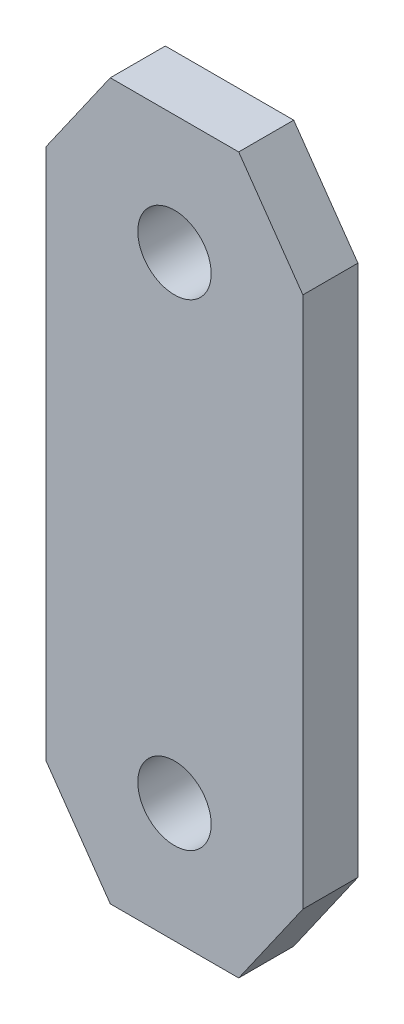
SolidWorks part; units mm, degrees
ref_plane "Płaszczyzna przednia" through (0, 0, 0) normal (0, 0, 1) x (1, 0, 0)
ref_plane "Płaszczyzna górna" through (0, 0, 0) normal (0, 1, 0) x (1, 0, 0)
ref_plane "Płaszczyzna prawa" through (0, 0, 0) normal (1, 0, 0) x (0, 0, -1)
sketch "Szkic1" plane through (0, 0, 0) normal (0, 0, 1) x (1, 0, 0)
  line L0 (7, 14.5) -> (3.5, 19.5)
  line L1 (3.5, -19.5) -> (-3.5, -19.5)
  line L2 (7, -14.5) -> (7, 14.5)
  line L3 (3.5, 19.5) -> (-3.5, 19.5)
  line L4 (-7, -14.5) -> (-7, 14.5)
  line L5 (7, -19.5) -> (-7, 19.5) construction
  line L6 (7, 19.5) -> (-7, -19.5) construction
  line L7 (-3.5, 19.5) -> (-7, 14.5)
  line L8 (-3.5, -19.5) -> (-7, -14.5)
  line L9 (7, -14.5) -> (3.5, -19.5)
  point P0 (0, 0)
  dimension "D1" = 39
  dimension "D2" = 14
  dimension "D3" = 3.5
  dimension "D4" = 5
  dimension "D5" = 3.5
  dimension "D6" = 5
  dimension "D7" = 3.5
  dimension "D8" = 5
  dimension "D9" = 3.5
  dimension "D10" = 5
extrude "Dodanie-wyciągnięcie1" add sketch "Szkic1" along normal blind 3
sketch "Szkic2" plane through (0, 0, 3) normal (0, 0, 1) x (1, 0, 0)
  circle A0 centre (0, 13) radius 2
  circle A1 centre (0, -13) radius 2
  point P4 (0, 0)
  dimension "D1" = 4
  dimension "D2" = 26
  dimension "D3" = 13
extrude "Wytnij-wyciągnięcie1" cut sketch "Szkic2" against normal blind 3
